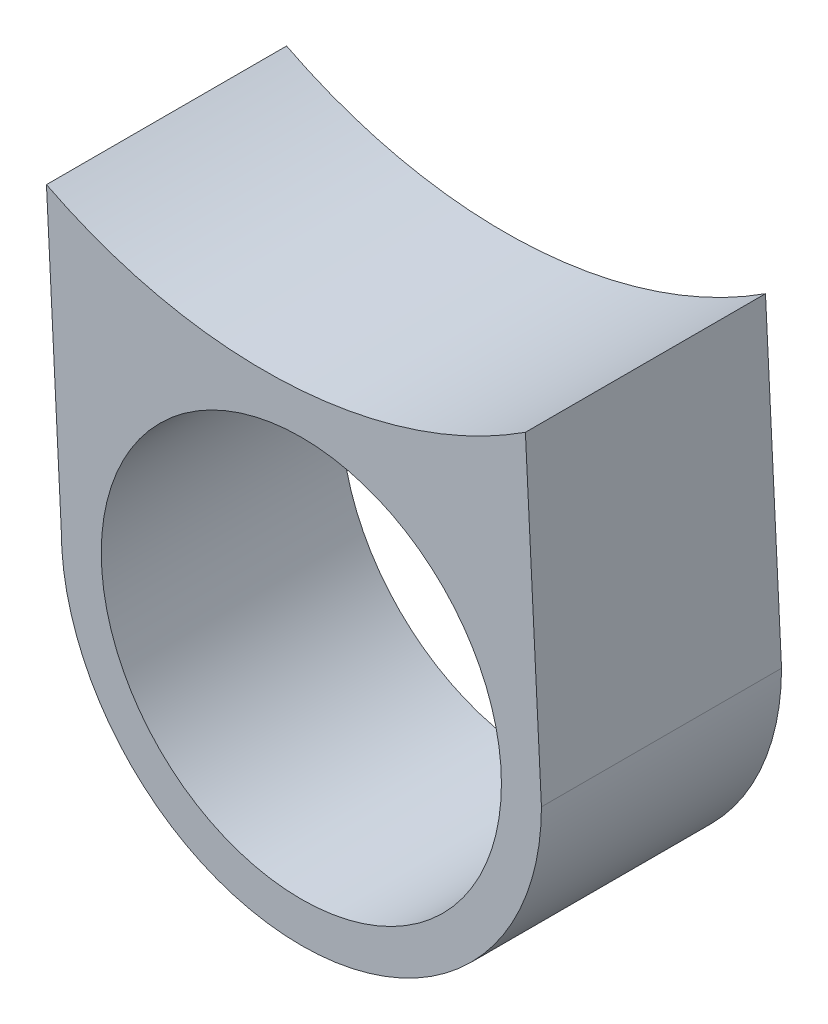
SolidWorks part; units mm, degrees
ref_plane "Front Plane" through (0, 0, 0) normal (0, 0, 1) x (1, 0, 0)
ref_plane "Top Plane" through (0, 0, 0) normal (0, 1, 0) x (1, 0, 0)
ref_plane "Right Plane" through (0, 0, 0) normal (1, 0, 0) x (0, 0, -1)
sketch "Sketch1" plane through (0, 0, 0) normal (0, 0, 1) x (1, 0, 0)
  line L0 (-43.9657, -46.4581) -> (-44.8892, -28.2544)
  line L1 (-13.9657, -46.4581) -> (-14.9683, -26.6943)
  line L2 (-16.4657, -46.4581) -> (-17.4987, -26.0951) construction
  line L3 (-16.4822, -45.8146) -> (-18.7987, -0.8743) construction
  circle A0 centre (-28.9657, -46.4581) radius 12.5 construction
  circle A1 centre (-28.9657, -46.4581) radius 12.5
  arc A2 (-43.9657, -46.4581) -> (-14.0427, -44.94) centre (-28.9657, -46.4581) ccw
  arc A4 (-44.8892, -28.2544) -> (-14.9683, -26.6943) centre (-31.2822, -1.5177) ccw
extrude "Boss-Extrude1" add sketch "Sketch1" against normal blind 10 and the other way blind 5
